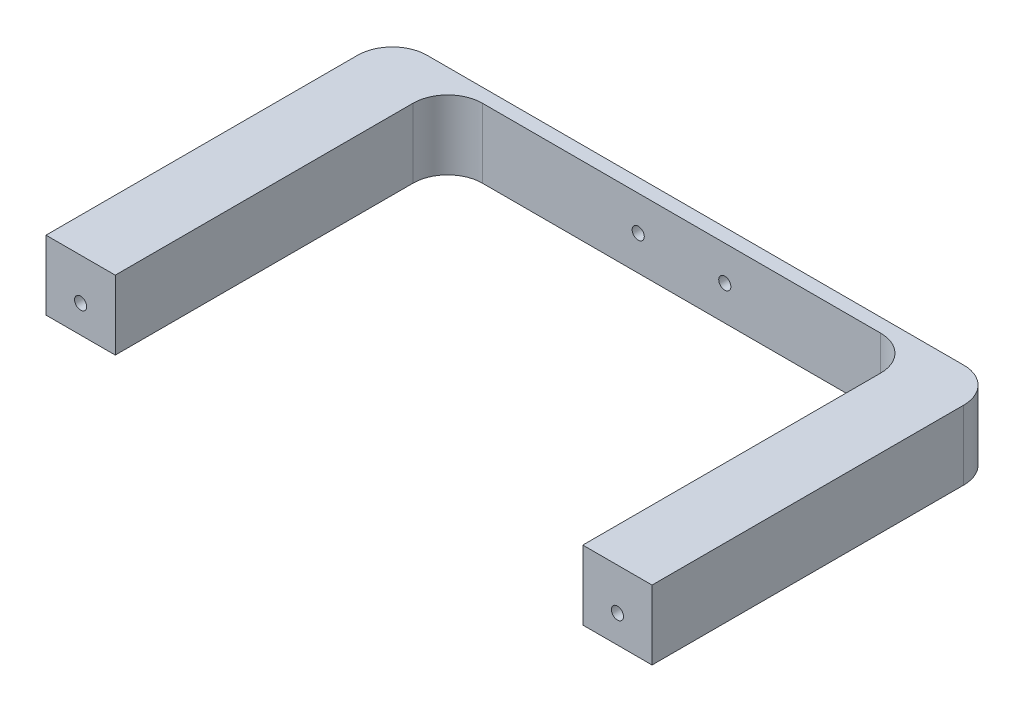
SolidWorks part; units mm, degrees
ref_plane "Front Plane" through (0, 0, 0) normal (0, 0, 1) x (1, 0, 0)
ref_plane "Top Plane" through (0, 0, 0) normal (0, 1, 0) x (1, 0, 0)
ref_plane "Right Plane" through (0, 0, 0) normal (1, 0, 0) x (0, 0, -1)
sketch "Sketch1" plane through (0, 0, 0) normal (0, 1, 0) x (1, 0, 0)
  line L0 (0, 0) -> (20, 0)
  line L1 (20, 0) -> (20, 96)
  line L2 (0, 0) -> (0, 100)
  line L3 (0, 100) -> (175, 100)
  line L4 (20, 96) -> (155, 96)
  line L5 (155, 96) -> (155, 0)
  line L6 (155, 0) -> (175, 0)
  line L7 (175, 0) -> (175, 100)
  line L8 (87.5, 96) -> (87.5, 100) construction
  dimension "D1" = 175
  dimension "D2" = 4
  dimension "D3" = 100
  dimension "D4" = 20
extrude "Boss-Extrude1" add sketch "Sketch1" along normal blind 20
fillet "Fillet1" radius 10 4 edges at (155, 10, -96) (20, 10, -96) (175, 10, -100) (0, 10, -100)
sketch "Sketch2" plane through (0, 0, -100) normal (0, 0, -1) x (-1, 0, 0)
  line L0 (-165, 20) -> (-165, 0) construction
  line L1 (-100, 10) -> (-75, 10) construction
  line L2 (-165, 0) -> (-10, 0) construction
  circle A0 centre (-100, 10) radius 1.75
  circle A1 centre (-75, 10) radius 1.75
  point P7 (-165, 10)
  point P9 (-87.5, 0)
  point P10 (-87.5, 10)
  dimension "D1" = 3.5
  dimension "D2" = 25
extrude "Cut-Extrude1" cut sketch "Sketch2" against normal through all
sketch "Sketch3" plane through (0, 0, 0) normal (0, -1, 0) x (1, 0, 0)
  line L2 (4, -4) -> (4, -28)
  line L3 (4, -28) -> (16, -28)
  line L4 (16, -4) -> (16, -28)
  line L5 (0, -90) -> (0, 0) construction
  line L6 (20, 0) -> (20, -86) construction
  line L7 (4, -4) -> (16, -4)
  line L8 (0, 0) -> (20, 0) construction
  dimension "D1" = 4
  dimension "D2" = 4
  dimension "D3" = 4
  dimension "D4" = 24
extrude "Cut-Extrude2" cut sketch "Sketch3" against normal blind 16
sketch "Sketch4" plane through (0, 0, -4) normal (0, 0, -1) x (-1, 0, 0)
  line L0 (-16, 16) -> (-16, 0) construction
  line L1 (-16, 16) -> (-4, 16) construction
  circle A0 centre (-10, 8) radius 1.75
  point P4 (-16, 8)
  point P7 (-10, 16)
  dimension "D1" = 3.5
extrude "Cut-Extrude3" cut sketch "Sketch4" against normal through all
ref_plane "Plane1" through (87.5, 0, 0) normal (1, 0, 0) x (0, 0, -1)
mirror "Mirror1" about plane through (87.5, 0, 0) normal (1, 0, 0) of "Cut-Extrude2", "Cut-Extrude3"
sketch "Sketch6" plane through (0, 0, -4) normal (0, 0, -1) x (-1, 0, 0)
  line L1 (-16, 16) -> (-4, 16)
  line L2 (-16, 16) -> (-16, 0)
  line L3 (-16, 0) -> (-4, 0)
  line L4 (-4, 16) -> (-4, 0)
extrude "Boss-Extrude2" add sketch "Sketch6" along normal blind 0.56
mirror "Mirror2" about plane through (87.5, 0, 0) normal (1, 0, 0) of "Boss-Extrude2"
